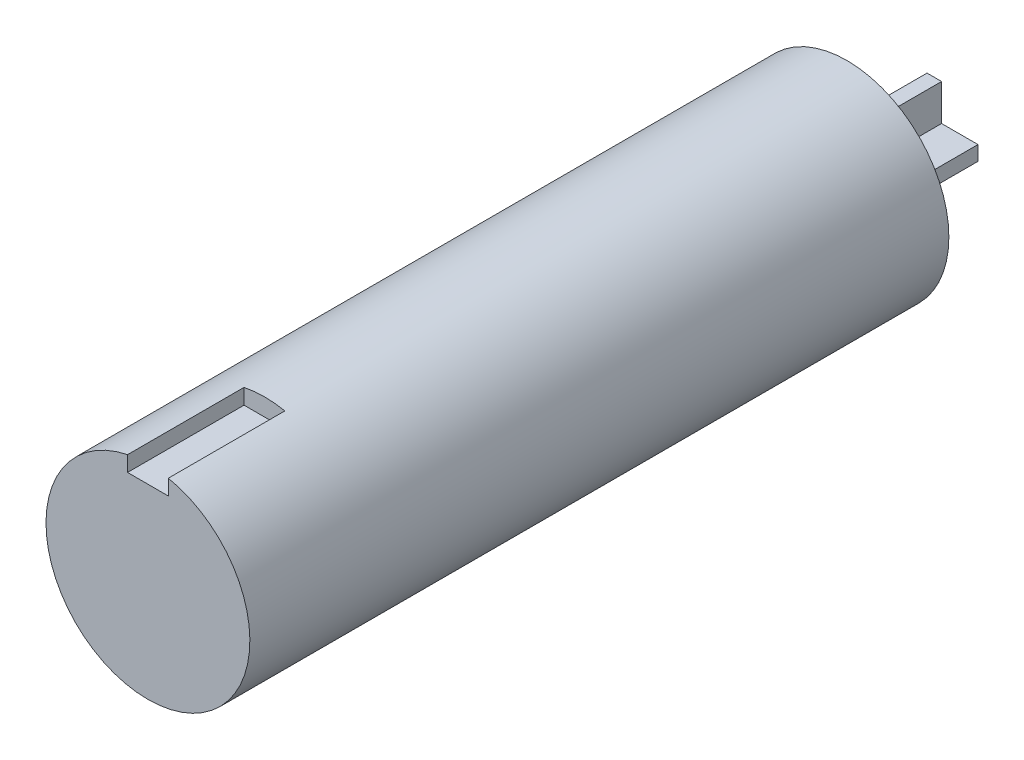
SolidWorks part; units mm, degrees
ref_plane "前视基准面" through (0, 0, 0) normal (0, 0, 1) x (1, 0, 0)
ref_plane "上视基准面" through (0, 0, 0) normal (0, 1, 0) x (1, 0, 0)
ref_plane "右视基准面" through (0, 0, 0) normal (1, 0, 0) x (0, 0, -1)
sketch "草图1" plane through (0, 0, 0) normal (0, 0, 1) x (1, 0, 0)
  line L1 (-1.25, -7.5) -> (1.25, -7.5)
  line L2 (-1.25, -7.5) -> (-1.25, 7.5)
  line L3 (-1.25, 7.5) -> (1.25, 7.5)
  line L4 (1.25, -7.5) -> (1.25, 7.5)
  line L5 (0, 7.5) -> (0, -7.5) construction
  line L6 (-1.25, 0) -> (1.25, 0) construction
  line L7 (-7.5, 1.25) -> (7.5, 1.25)
  line L8 (-7.5, 1.25) -> (-7.5, -1.25)
  line L9 (-7.5, -1.25) -> (7.5, -1.25)
  line L10 (7.5, 1.25) -> (7.5, -1.25)
  line L11 (0, -1.25) -> (0, 1.25) construction
  line L12 (-7.5, 0) -> (7.5, 0) construction
  point P0 (0, 0)
  point P4 (0, 0)
extrude "凸台-拉伸1" add sketch "草图1" against normal blind 15 contours L2 L7 L4 L3 | L8 L9 L2 L7 | L10 L7 L4 L9 | L9 L2 L1 L4 | L2 L9 L4 L7
sketch "草图2" plane through (0, 0, 0) normal (0, 0, 1) x (1, 0, 0)
  circle A0 centre (0, 0) radius 17.5
  dimension "D1" = 35
extrude "凸台-拉伸2" add sketch "草图2" along normal blind 120
ref_plane "基准面1" through (0, 17.5, 0) normal (0, 1, 0) x (1, 0, 0)
sketch "草图3" plane through (0, 17.5, 0) normal (0, 1, 0) x (1, 0, 0)
  line L0 (-17.5, -120) -> (17.5, -120) construction
  line L1 (-3.5, -100) -> (3.5, -100)
  line L2 (-3.5, -100) -> (-3.5, -120)
  line L3 (-3.5, -120) -> (3.5, -120)
  line L4 (3.5, -100) -> (3.5, -120)
  line L5 (0, -120) -> (0, -100) construction
  line L6 (-3.5, -110) -> (3.5, -110) construction
  point P0 (0, -110)
  dimension "D1" = 7
  dimension "D2" = 20
extrude "切除-拉伸1" cut sketch "草图3" against normal blind 3
